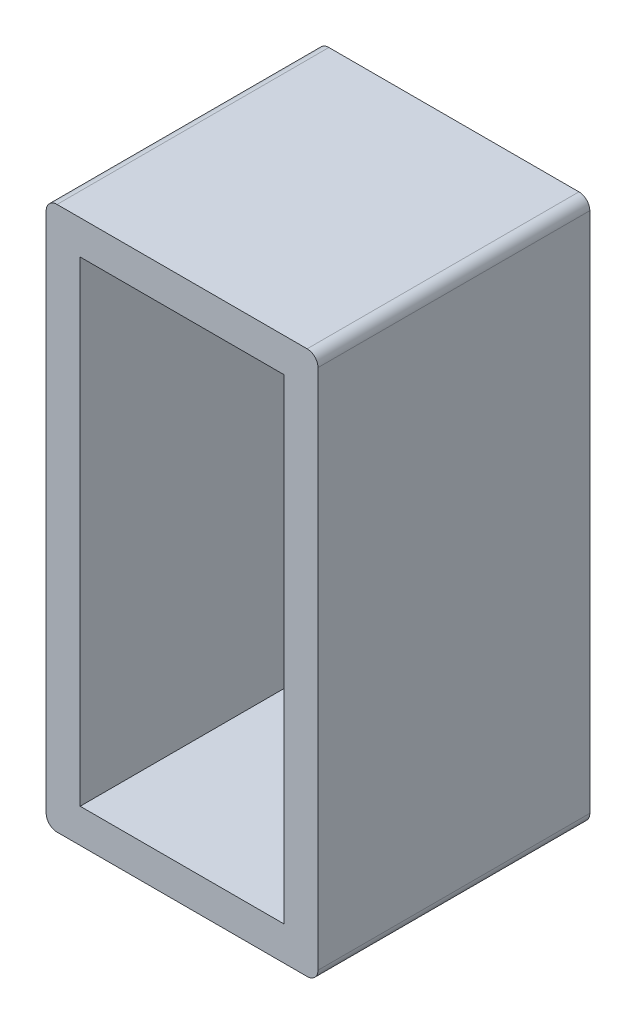
SolidWorks part; units mm, degrees
ref_plane "Front Plane" through (0, 0, 0) normal (0, 0, 1) x (1, 0, 0)
ref_plane "Top Plane" through (0, 0, 0) normal (0, 1, 0) x (1, 0, 0)
ref_plane "Right Plane" through (0, 0, 0) normal (1, 0, 0) x (0, 0, -1)
sketch "Sketch1" plane through (0, 0, 0) normal (0, 0, 1) x (1, 0, 0)
  line L0 (-9.525, 22.225) -> (9.525, 22.225)
  line L1 (-11.684, -25.4) -> (11.684, -25.4)
  line L2 (-12.7, -24.384) -> (-12.7, 24.384)
  line L3 (-11.684, 25.4) -> (11.684, 25.4)
  line L4 (12.7, -24.384) -> (12.7, 24.384)
  line L5 (-12.7, -25.4) -> (12.7, 25.4) construction
  line L6 (-12.7, 25.4) -> (12.7, -25.4) construction
  line L7 (9.525, -22.225) -> (9.525, 22.225)
  line L8 (-9.525, -22.225) -> (9.525, -22.225)
  line L9 (-9.525, -22.225) -> (-9.525, 22.225)
  arc A0 (-12.7, -24.384) -> (-11.684, -25.4) centre (-11.684, -24.384) ccw
  arc A1 (11.684, -25.4) -> (12.7, -24.384) centre (11.684, -24.384) ccw
  arc A2 (12.7, 24.384) -> (11.684, 25.4) centre (11.684, 24.384) ccw
  arc A3 (-11.684, 25.4) -> (-12.7, 24.384) centre (-11.684, 24.384) ccw
  arc A4 (9.525, 22.225) -> (9.525, 22.225) centre (9.525, 22.225) ccw
  arc A5 (9.525, -22.225) -> (9.525, -22.225) centre (9.525, -22.225) ccw
  arc A6 (-9.525, -22.225) -> (-9.525, -22.225) centre (-9.525, -22.225) ccw
  arc A7 (-9.525, 22.225) -> (-9.525, 22.225) centre (-9.525, 22.225) ccw
  point P0 (0, 0)
  dimension "D3" = 1.016
  dimension "D1" = 25.4
  dimension "D2" = 50.8
  dimension "D4" = 3.175
extrude "Boss-Extrude1" add sketch "Sketch1" along normal mid plane 25.4
